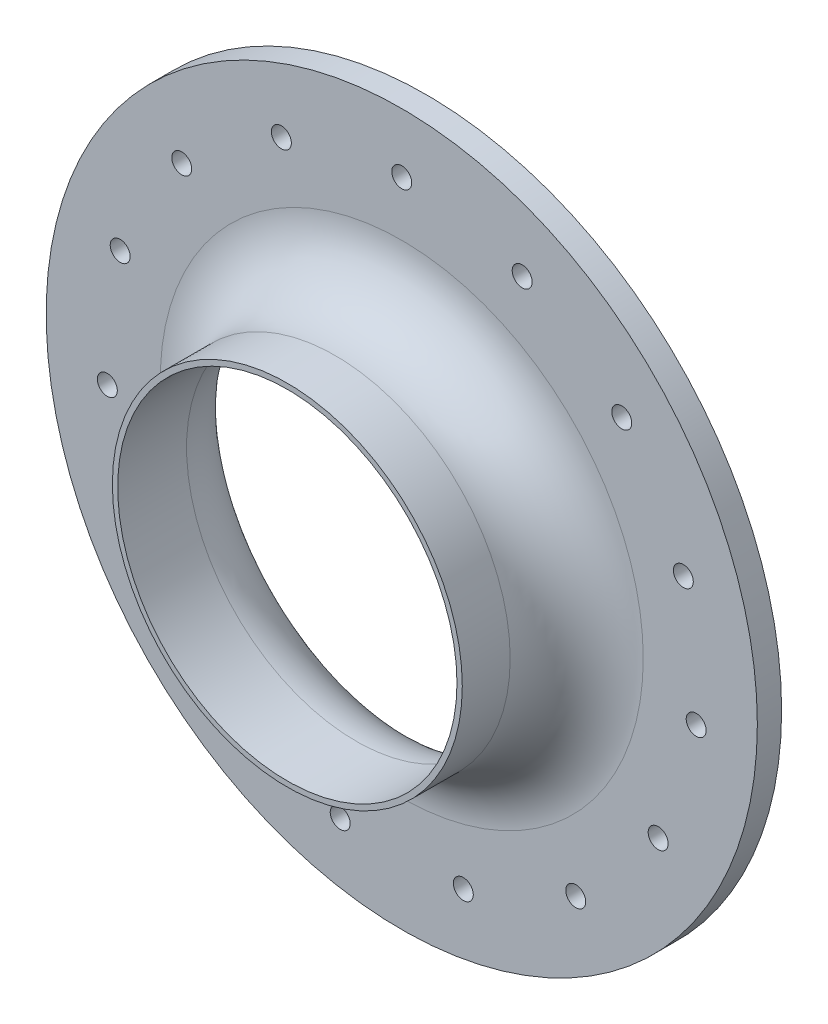
SolidWorks part; units mm, degrees
ref_plane "Plan1" through (0, 0, 0) normal (0, 0, 1) x (1, 0, 0)
ref_plane "Plan2" through (0, 0, 0) normal (0, 1, 0) x (1, 0, 0)
ref_plane "Plan3" through (0, 0, 0) normal (1, 0, 0) x (0, 0, -1)
sketch "Esquisse1" plane through (0, 0, 0) normal (1, 0, 0) x (0, 0, -1)
  line L0 (0, 0) -> (105.4524, 0) construction
  line L1 (20.85, 46.5) -> (20.85, 53.45)
  line L2 (20.85, 53.45) -> (17.2, 53.45)
  line L3 (0, 25.5) -> (0, 26.3)
  line L4 (0, 26.3) -> (7.2, 26.3)
  line L5 (17.2, 36.3) -> (17.2, 53.45)
  line L12 (20.85, 46.5) -> (20.85, 36)
  line L13 (1.5, 25.5) -> (-21.1015, 25.5) construction
  line L14 (1.5, 25.5) -> (10.35, 25.5)
  line L15 (1.5, 25.5) -> (0, 25.5)
  arc A0 (7.2, 26.3) -> (17.2, 36.3) centre (7.2, 36.3) ccw
  arc A2 (10.35, 25.5) -> (20.85, 36) centre (10.35, 36) ccw
  dimension "D15" = 72
  dimension "D16" = 3.6643
  dimension "D2" = 7.2
  dimension "D3" = 52.6
  dimension "D5" = 51
  dimension "D14" = 93
  dimension "D17" = 8.85
revolve "Base-Révolution" add sketch "Esquisse1" angle 360 about L0
sketch "Esquisse2" plane through (0, 0, -17.2) normal (0, 0, 1) x (1, 0, 0)
  line L0 (0, 0) -> (0, 44.5) construction
  circle A0 centre (0, 44.5) radius 1.5
  circle A1 centre (18.0998, 40.6528) radius 1.5
  circle A2 centre (33.0699, 29.7763) radius 1.5
  circle A3 centre (42.322, 13.7513) radius 1.5
  circle A4 centre (44.2562, -4.6515) radius 1.5
  circle A5 centre (38.5381, -22.25) radius 1.5
  circle A6 centre (26.1564, -36.0013) radius 1.5
  circle A7 centre (9.2521, -43.5276) radius 1.5
  circle A8 centre (-9.2521, -43.5276) radius 1.5
  circle A9 centre (-26.1564, -36.0013) radius 1.5
  circle A10 centre (-38.5381, -22.25) radius 1.5
  circle A11 centre (-44.2562, -4.6515) radius 1.5
  circle A12 centre (-42.322, 13.7513) radius 1.5
  circle A13 centre (-33.0699, 29.7763) radius 1.5
  circle A14 centre (-18.0998, 40.6528) radius 1.5
  dimension "D1" = 3
  dimension "D2" = 44.5
  dimension "D3" = 44.5
extrude "Enlèv. mat.-Extru.1" cut sketch "Esquisse2" against normal through all
ref_plane "Plan4" through (0, 57.5, 0) normal (0, 1, 0) x (-1, 0, 0)
